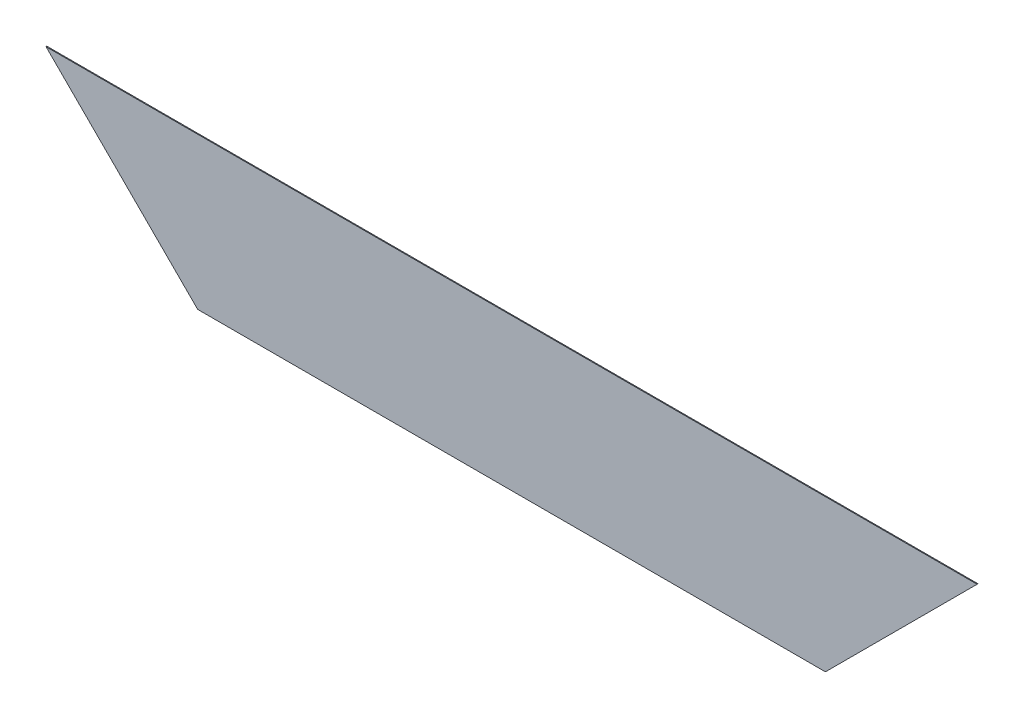
SolidWorks part; units mm, degrees
ref_plane "Front Plane" through (0, 0, 0) normal (0, 0, 1) x (1, 0, 0)
ref_plane "Top Plane" through (0, 0, 0) normal (0, 1, 0) x (1, 0, 0)
ref_plane "Right Plane" through (0, 0, 0) normal (1, 0, 0) x (0, 0, -1)
sketch "Sketch1" plane through (0, 0, 0) normal (0, 0, 1) x (1, 0, 0)
  line L0 (-13.35, 2.175) -> (-9, -2.175)
  line L1 (-13.35, 2.175) -> (13.35, 2.175)
  line L2 (13.35, 2.175) -> (9, -2.175)
  line L3 (-9, -2.175) -> (9, -2.175)
  line L7 (0, 7.7393) -> (0, -6.5673) construction
  point P0 (0, 0)
  dimension "D1" = 26.7
  dimension "D3" = 45
extrude "Boss-Extrude1" add sketch "Sketch1" along normal blind 0.025
